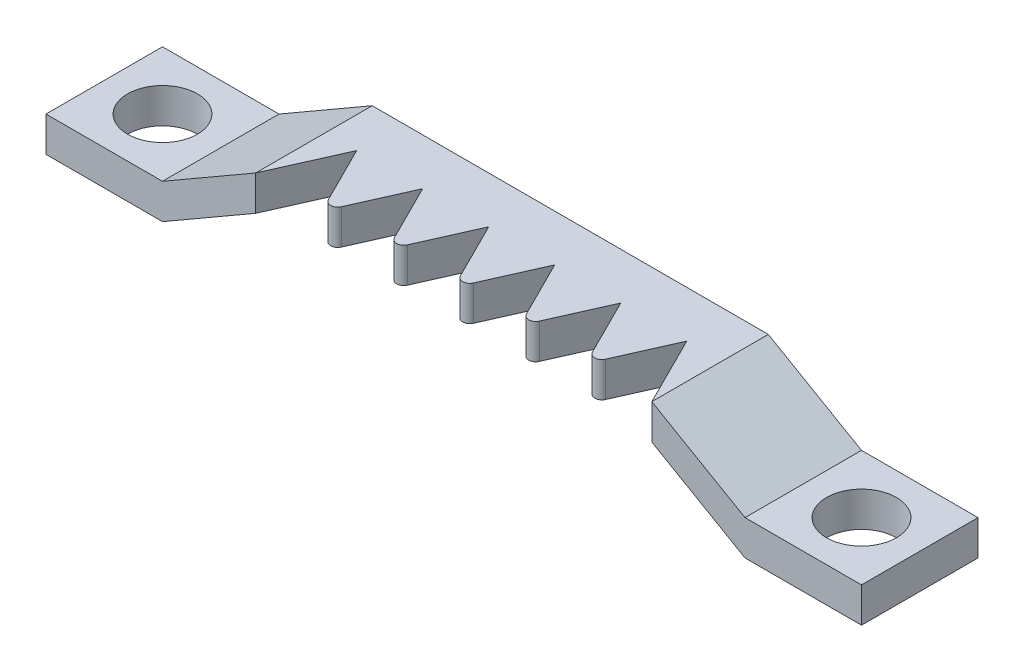
SolidWorks part; units mm, degrees
material "Copper"
ref_plane "Front Plane" through (0, 0, 0) normal (0, 0, 1) x (1, 0, 0)
ref_plane "Top Plane" through (0, 0, 0) normal (0, 1, 0) x (1, 0, 0)
ref_plane "Right Plane" through (0, 0, 0) normal (1, 0, 0) x (0, 0, -1)
sketch "Sketch1" plane through (0, 0, 0) normal (0, 0, 1) x (1, 0, 0)
  line L0 (0, 0) -> (6.35, 0)
  line L1 (6.35, 0) -> (11.43, 2.9329)
  line L2 (11.43, 2.9329) -> (33.02, 2.9329)
  line L3 (33.02, 2.9329) -> (38.1, 0)
  line L4 (38.1, 0) -> (44.45, 0)
  line L5 (44.45, 0) -> (44.45, 1.905)
  line L6 (44.45, 1.905) -> (38.1, 1.905)
  line L7 (38.1, 1.905) -> (33.02, 4.8379)
  line L8 (33.02, 4.8379) -> (11.43, 4.8379)
  line L9 (11.43, 4.8379) -> (6.35, 1.905)
  line L10 (6.35, 1.905) -> (0, 1.905)
  line L11 (0, 1.905) -> (0, 0)
  point P3 (0, 0)
  point P14 (0, 0)
  point P15 (0, 0)
  point P16 (0, 0)
  point P17 (0, 0)
  dimension "D1" = 30
  dimension "D2" = 5.08
  dimension "D3" = 44.45
  dimension "D4" = 1.905
  dimension "D5" = 6.35
extrude "Base Extrude" add sketch "Sketch1" along normal blind 6.35
sketch "Sketch2" plane through (0, 4.8379, 0) normal (0, 1, 0) x (1, 0, 0)
  line L0 (44.45, -6.35) -> (44.45, 0) construction
  line L1 (44.45, -6.35) -> (38.1, -6.35) construction
  line L2 (22.225, -6.35) -> (22.225, 0) construction
  line L3 (33.02, -6.35) -> (11.43, -6.35) construction
  line L4 (33.02, 0) -> (11.43, 0) construction
  circle A0 centre (41.275, -3.175) radius 1.905
  circle A1 centre (3.175, -3.175) radius 1.905
  dimension "D3" = 3.81
  dimension "D1" = 3.175
  dimension "D2" = 3.175
extrude "Hole Cuts" cut sketch "Sketch2" against normal up to next
sketch "Sketch3" plane through (0, 4.8379, 0) normal (0, 1, 0) x (1, 0, 0)
  line L2 (33.02, -6.35) -> (31.115, -2.54)
  line L12 (31.115, -2.54) -> (29.4217, -6.35)
  line L13 (33.02, -6.35) -> (11.43, -6.35) construction
  line L14 (27.5167, -2.54) -> (25.8233, -6.35)
  line L15 (29.4217, -6.35) -> (27.5167, -2.54)
  line L16 (23.9183, -2.54) -> (22.225, -6.35)
  line L17 (25.8233, -6.35) -> (23.9183, -2.54)
  line L18 (20.32, -2.54) -> (18.6267, -6.35)
  line L19 (22.225, -6.35) -> (20.32, -2.54)
  line L20 (16.7217, -2.54) -> (15.0283, -6.35)
  line L21 (18.6267, -6.35) -> (16.7217, -2.54)
  line L22 (13.1233, -2.54) -> (11.43, -6.35)
  line L23 (15.0283, -6.35) -> (13.1233, -2.54)
  line L25 (33.02, -6.35) -> (11.43, -6.35)
  line M3 (11.43, -6.35) -> (33.02, -6.35)
  dimension "D1" = 3.5983
  dimension "D2" = 3.81
  dimension "D3" = 1.905
  dimension "D4" = 6
extrude "Teeth Cuts" cut sketch "Sketch3" against normal up to next contours L15 L14 M3 | L2 L12 M3 | L17 L16 M3 | L19 L18 M3 | L21 L20 M3 | L23 L22 M3
fillet "Teeth Fillet" radius 0.381 5 edges at (15.0283, 3.8854, 6.35) (18.6267, 3.8854, 6.35) (22.225, 3.8854, 6.35) (25.8233, 3.8854, 6.35) (29.4217, 3.8854, 6.35)
